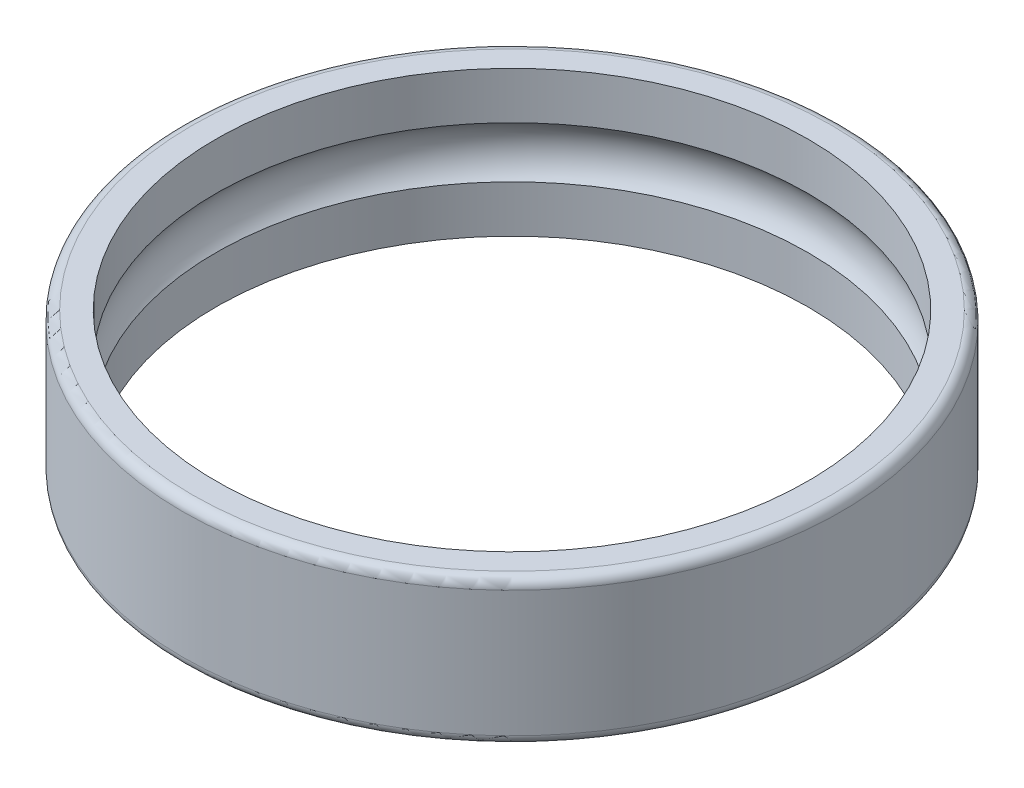
SolidWorks part; units mm, degrees
ref_plane "Front Plane" through (0, 0, 0) normal (0, 0, 1) x (1, 0, 0)
ref_plane "Top Plane" through (0, 0, 0) normal (0, 1, 0) x (1, 0, 0)
ref_plane "Right Plane" through (0, 0, 0) normal (1, 0, 0) x (0, 0, -1)
sketch "Sketch1" plane through (0, 0, 0) normal (0, 0, 1) x (1, 0, 0)
  line L0 (0, 0) -> (0, 46.1124) construction
  line L1 (-30.55, 7.5) -> (-24.625, 7.5) construction
  line L2 (-30.55, 0) -> (-34, 0)
  line L3 (-30.55, 0) -> (-30.55, 15)
  line L4 (-30.55, 15) -> (-34, 15)
  line L5 (-34, 0) -> (-34, 15)
  line L6 (-24.625, 0) -> (-20, 0)
  line L7 (-24.625, 0) -> (-24.625, 15)
  line L8 (-24.625, 15) -> (-20, 15)
  line L9 (-20, 0) -> (-20, 15)
  circle A0 centre (-27.5875, 7.5) radius 3.9688
  dimension "D6" = 7.9375
  dimension "D1" = 15
  dimension "D2" = 34
  dimension "D3" = 30.55
  dimension "D4" = 20
  dimension "D5" = 24.625
revolve "Revolve1" add sketch "Sketch1" angle 360 about L0
fillet "Fillet1" radius 1 2 edges at (0, 0, -34) (0, 15, -34)
